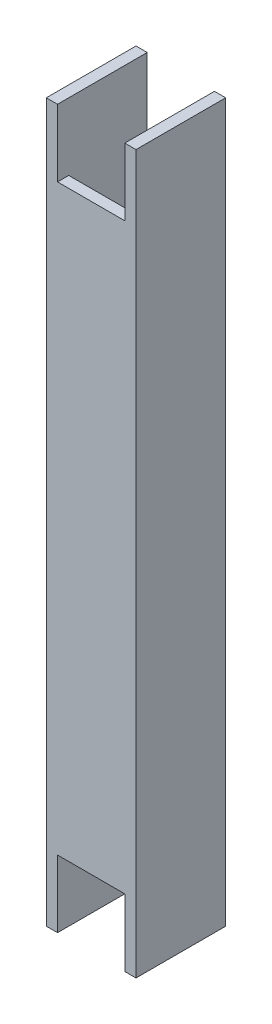
SolidWorks part; units mm, degrees
ref_plane "Front Plane" through (0, 0, 0) normal (0, 0, 1) x (1, 0, 0)
ref_plane "Top Plane" through (0, 0, 0) normal (0, 1, 0) x (1, 0, 0)
ref_plane "Right Plane" through (0, 0, 0) normal (1, 0, 0) x (0, 0, -1)
sketch "Sketch1" plane through (0, 0, 0) normal (0, 1, 0) x (1, 0, 0)
  line L1 (0, 0) -> (25.4, 0)
  line L2 (0, 0) -> (0, 25.4)
  line L3 (0, 25.4) -> (25.4, 25.4)
  line L4 (25.4, 0) -> (25.4, 25.4)
  dimension "D1" = 25.4
  dimension "D2" = 25.4
extrude "Extrude-Thin1" add sketch "Sketch1" along normal blind 203.2 thin thin type one direction reverse wall 3.175
sketch "Sketch3" plane through (0, 0, 0) normal (0, 0, 1) x (1, 0, 0)
  line L0 (0, 203.2) -> (25.4, 203.2) construction
  line L1 (3.175, 203.2) -> (22.225, 203.2)
  line L2 (3.175, 203.2) -> (3.175, 184.15)
  line L3 (3.175, 184.15) -> (22.225, 184.15)
  line L4 (22.225, 203.2) -> (22.225, 184.15)
  line L5 (0, 203.2) -> (0, 0) construction
  line L6 (25.4, 203.2) -> (25.4, 0) construction
  dimension "D1" = 3.175
  dimension "D2" = 3.175
  dimension "D3" = 19.05
extrude "Cut-Extrude1" cut sketch "Sketch3" against normal through all
sketch "Sketch4" plane through (0, 0, 0) normal (0, 0, 1) x (1, 0, 0)
  line L0 (0, 0) -> (25.4, 0) construction
  line L1 (3.175, 0) -> (22.225, 0)
  line L2 (3.175, 0) -> (3.175, 19.05)
  line L3 (3.175, 19.05) -> (22.225, 19.05)
  line L4 (22.225, 0) -> (22.225, 19.05)
  line L5 (0, 203.2) -> (0, 0) construction
  line L6 (25.4, 203.2) -> (25.4, 0) construction
  dimension "D1" = 3.175
  dimension "D2" = 3.175
  dimension "D3" = 19.05
extrude "Cut-Extrude2" cut sketch "Sketch4" against normal through all
